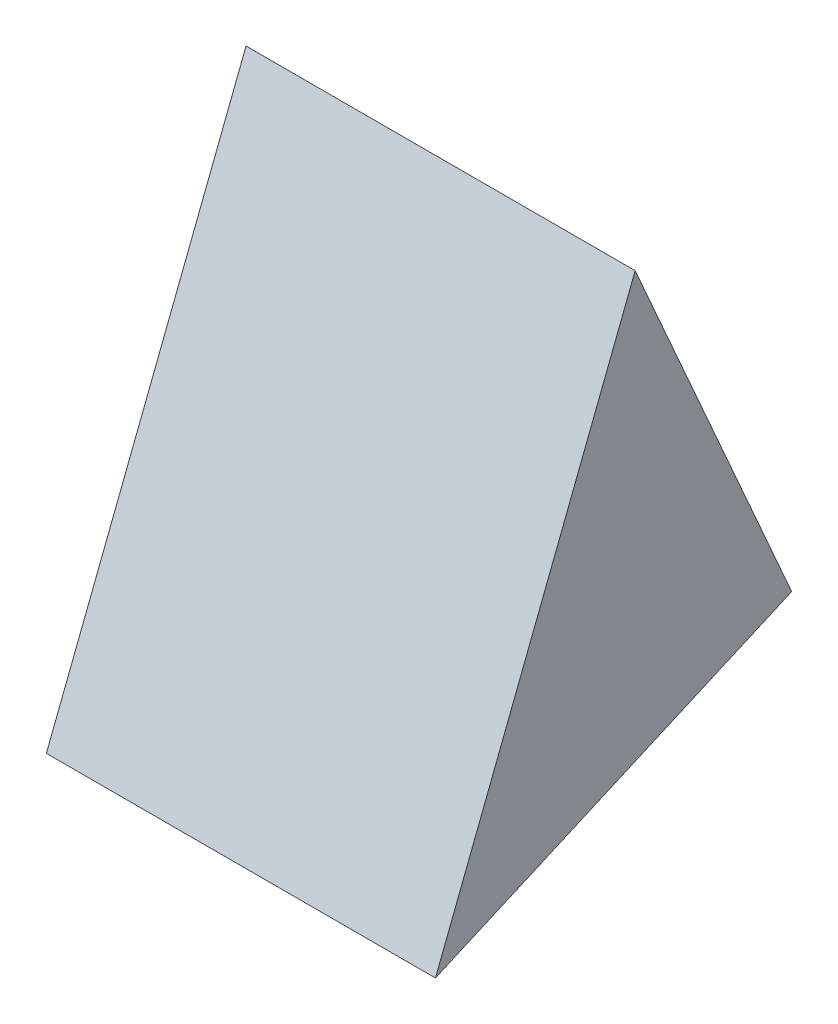
SolidWorks part; units mm, degrees
material "AISI 1010 Steel, hot rolled bar"
ref_plane "Front Plane" through (0, 0, 0) normal (0, 0, 1) x (1, 0, 0)
ref_plane "Top Plane" through (0, 0, 0) normal (0, 1, 0) x (1, 0, 0)
ref_plane "Right Plane" through (0, 0, 0) normal (1, 0, 0) x (0, 0, -1)
sketch "Sketch1" plane through (0, 0, 0) normal (1, 0, 0) x (0, 0, -1)
  line L0 (-17.1748, 16.8577) -> (-32.5728, -22.6759)
  line L1 (-32.5728, -22.6759) -> (-5.107, -10.6081)
  line L2 (-5.107, -10.6081) -> (-17.1748, 16.8577)
  dimension "D1" = 30
extrude "Boss-Extrude1" add sketch "Sketch1" along normal blind 30
